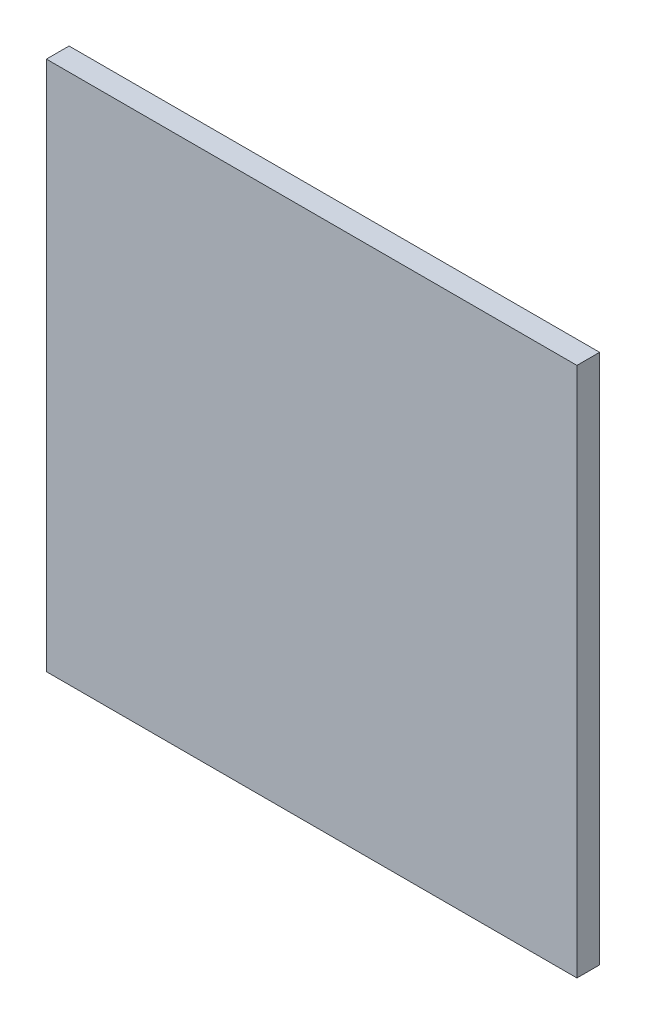
SolidWorks part; units mm, degrees
ref_plane "Front Plane" through (0, 0, 0) normal (0, 0, 1) x (1, 0, 0)
ref_plane "Top Plane" through (0, 0, 0) normal (0, 1, 0) x (1, 0, 0)
ref_plane "Right Plane" through (0, 0, 0) normal (1, 0, 0) x (0, 0, -1)
sketch "Sketch2" plane through (0, 0, 0) normal (0, 0, 1) x (1, 0, 0)
  line L1 (0, 0) -> (11.7, 0)
  line L2 (0, 0) -> (0, -11.7)
  line L3 (0, -11.7) -> (11.7, -11.7)
  line L4 (11.7, 0) -> (11.7, -11.7)
  dimension "D1" = 11.7
extrude "Boss-Extrude1" add sketch "Sketch2" along normal blind 0.5
